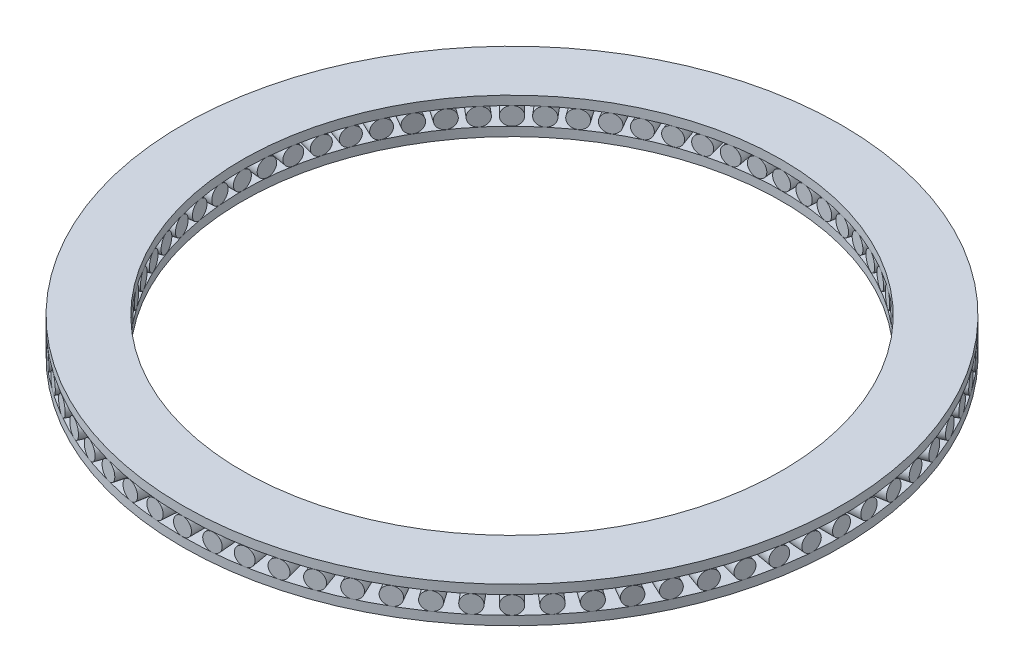
SolidWorks part; units mm, degrees
ref_plane "前视基准面" through (0, 0, 0) normal (0, 0, 1) x (1, 0, 0)
ref_plane "上视基准面" through (0, 0, 0) normal (0, 1, 0) x (1, 0, 0)
ref_plane "右视基准面" through (0, 0, 0) normal (1, 0, 0) x (0, 0, -1)
sketch "草图1" plane through (0, 0, 0) normal (0, 1, 0) x (1, 0, 0)
  circle A0 centre (0, 0) radius 55
  circle A1 centre (0, 0) radius 45
  dimension "D1" = 110
  dimension "D2" = 90
extrude "凸台-拉伸1" add sketch "草图1" along normal blind 1.5
sketch "草图2" plane through (0, 0, 0) normal (0, 0, 1) x (1, 0, 0)
  circle A0 centre (0, 3) radius 1.5
  point P0 (0, 0)
extrude "凸台-拉伸2" add sketch "草图2" along normal blind 10 from offset 45 separate body
pattern_circular "阵列(圆周)3" count 72 over 360 about axis through (0, 0, 0) along (0, 1, 0)
sketch "草图3" plane through (0, 0, 0) normal (0, -1, 0) x (1, 0, 0)
  circle A0 centre (0, 0) radius 55
  circle A1 centre (0, 0) radius 45
  dimension "D1" = 90
  dimension "D2" = 110
extrude "凸台-拉伸3" add sketch "草图3" against normal blind 1.5 from offset 4.5 separate body
